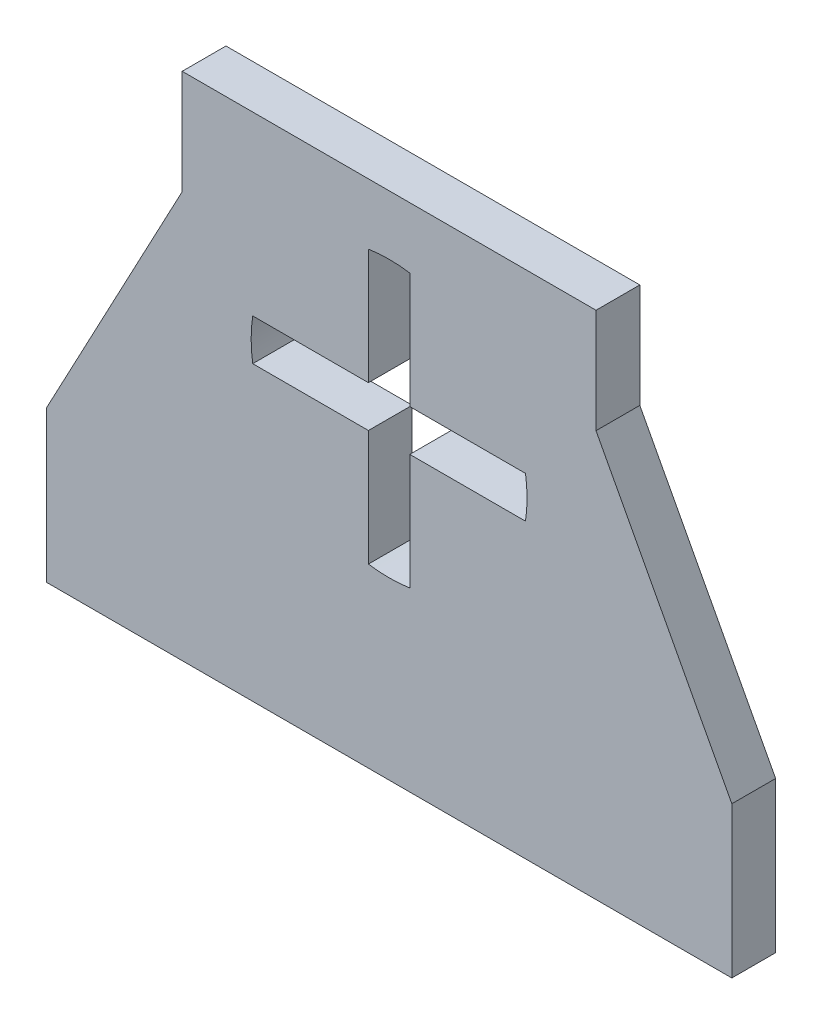
SolidWorks part; units mm, degrees
ref_plane "Front Plane" through (0, 0, 0) normal (0, 0, 1) x (1, 0, 0)
ref_plane "Top Plane" through (0, 0, 0) normal (0, 1, 0) x (1, 0, 0)
ref_plane "Right Plane" through (0, 0, 0) normal (1, 0, 0) x (0, 0, -1)
sketch "Sketch1" plane through (0, 0, 0) normal (0, 0, 1) x (1, 0, 0)
  line L1 (-24.845, 13.5) -> (24.845, 13.5)
  line L2 (-24.845, 13.5) -> (-24.845, -13.5)
  line L3 (-24.845, -13.5) -> (24.845, -13.5)
  line L4 (24.845, 13.5) -> (24.845, -13.5)
  line L5 (-24.845, 13.5) -> (24.845, -13.5) construction
  line L6 (-24.845, -13.5) -> (24.845, 13.5) construction
  point P0 (0, 0)
  dimension "D1" = 27
  dimension "D2" = 49.69
extrude "Boss-Extrude1" add sketch "Sketch1" along normal blind 3.175
sketch "Sketch2" plane through (0, 0, 0) normal (0, 0, 1) x (1, 0, 0)
  line L0 (24.845, -13.5) -> (-24.845, -13.5)
  line L1 (-24.845, -13.5) -> (-24.845, 13.5)
  line L2 (-24.845, 13.5) -> (24.845, 13.5)
  line L4 (24.845, 0) -> (24.845, 13.5)
  line L5 (24.845, 0) -> (24.845, -13.5)
  line L9 (0, 13.5) -> (10, 13.5)
  line L10 (0, 13.5) -> (-10, 13.5)
  line L11 (10, 13.5) -> (10, 6.75)
  line L12 (-10, 13.5) -> (-10, 6.75)
  line L13 (-10, 6.75) -> (-24.845, -6.75)
  line L14 (10, 6.75) -> (24.845, -6.75)
  dimension "D1" = 10
  dimension "D2" = 10
extrude "Cut-Extrude1" cut sketch "Sketch2" along normal blind 3.175 contours L11 L14 L5 L4 L2 | L13 L12 L2 L1
sketch "Sketch3" plane through (0, 0, 0) normal (0, 0, -1) x (-1, 0, 0)
  line L0 (-24.845, -13.5) -> (24.845, -13.5)
  line L1 (-10, 13.5) -> (-10, 23.5)
  line L2 (0, -0.8) -> (0, 9.2)
  line L3 (-24.845, -13.5) -> (-24.845, -6.75)
  line L4 (-24.845, -6.75) -> (-10, 6.75)
  line L5 (-10, 6.75) -> (-10, 13.5)
  line L6 (-10, 13.5) -> (10, 13.5)
  line L7 (10, 13.5) -> (10, 6.75)
  line L8 (10, 6.75) -> (24.845, -6.75)
  line L9 (24.845, -6.75) -> (24.845, -13.5)
  line L10 (10, 13.5) -> (10, 23.5)
  line L12 (10, 23.5) -> (-10, 23.5)
  line L13 (-10, 23.5) -> (-15, 23.5)
  line L14 (-15, 23.5) -> (-15, 15.9375)
  line L15 (15, 23.5) -> (15, 15.9375)
  line L16 (10, 23.5) -> (15, 23.5)
  line L20 (24.845, -2.5625) -> (24.845, -6.75)
  line L22 (-24.845, -2.5625) -> (-24.845, -13.5)
  line L23 (-24.845, -2.5625) -> (-15, 15.9375)
  line L24 (24.845, -2.5625) -> (15, 15.9375)
  circle A0 centre (0, 9.2) radius 10
  line M17 (-10, 13.5) -> (-10, 6.75)
  line M18 (-10, 6.75) -> (-24.845, -6.75)
  line M22 (24.845, -6.75) -> (10, 6.75)
  line M23 (10, 6.75) -> (10, 13.5)
  line M24 (10, 13.5) -> (-10, 13.5)
  dimension "D3" = 20
  dimension "D4" = 10
  dimension "D5" = 5
extrude "Boss-Extrude2" add sketch "Sketch3" against normal blind 3.175 contours L23 L22 L5 L1 L13 L14 M18 M17 | L20 L24 L15 L16 L10 L7 M23 M22 | A0 L10 L12 L1 M24
sketch "Sketch4" plane through (0, 0, 0) normal (0, 0, -1) x (-1, 0, 0)
  line L0 (-24.845, -13.5) -> (24.845, -13.5)
  line L1 (0, -13.5) -> (0, -3.8)
  line L2 (0, -3.8) -> (0, 9.2)
  circle A0 centre (0, 9.2) radius 10
  dimension "D3" = 20
  dimension "D1" = 9.7
  dimension "D2" = 13
extrude "Boss-Extrude3" add sketch "Sketch4" against normal blind 3.175
sketch "Sketch5" plane through (0, 0, 0) normal (0, 0, -1) x (-1, 0, 0)
  line L0 (0, -13.5) -> (0, -3.8)
  line L1 (24.845, -13.5) -> (-24.845, -13.5) construction
  line L2 (0, -3.8) -> (0, -0.8)
  line L5 (1, 10.2) -> (1, 19.1499)
  line L6 (1, 8.2) -> (1, -0.7499)
  line L7 (-1, 8.2) -> (-1, -0.7499)
  line L8 (-1, 10.2) -> (-1, 19.1499)
  line L11 (-9.9499, 8.2) -> (-1, 8.2)
  line L12 (-9.9499, 10.2) -> (-1, 10.2)
  line L14 (1, 8.2) -> (9.9499, 8.2)
  line L15 (1, 10.2) -> (9.9499, 10.2)
  circle A0 centre (0, 9.2) radius 10
  point P10 (0, 9.2)
  point P13 (0, 9.2)
  dimension "D3" = 20
  dimension "D1" = 9.7
  dimension "D2" = 13
extrude "Cut-Extrude2" cut sketch "Sketch5" against normal blind 3.175 contours L5 A0 L8 L12 L11 L7 L6 L14 L15
sketch "Sketch6" plane through (0, 0, 0) normal (0, 0, -1) x (-1, 0, 0)
  line L1 (10, 9.2) -> (8.2649, 9.2)
  line L2 (1.5, 19.0869) -> (1.5, 10.7)
  line L3 (1, -0.7499) -> (1, 8.2)
  line L5 (1.5, -0.6869) -> (1.5, 7.7)
  line L6 (1, 8.2) -> (9.9499, 8.2)
  line L7 (9.9499, 10.2) -> (1, 10.2)
  line L9 (-1.5, -0.6869) -> (-1.5, 7.7)
  line L10 (-1.5, 19.0869) -> (-1.5, 10.7)
  line L13 (9.8869, 7.7) -> (1.5, 7.7)
  line L14 (1, 10.2) -> (1, 19.1499)
  line L16 (-9.8869, 7.7) -> (-1.5, 7.7)
  line L18 (9.8869, 10.7) -> (1.5, 10.7)
  line L20 (-9.8869, 10.7) -> (-1.5, 10.7)
  line L21 (-1, 19.1499) -> (-1, 10.2)
  line L22 (-1, 10.2) -> (-9.9499, 10.2)
  line L23 (-9.9499, 8.2) -> (-1, 8.2)
  line L24 (-1, 8.2) -> (-1, -0.7499)
  line L25 (1, 8.2) -> (-1, 10.2)
  line L26 (-1, 8.2) -> (1, 10.2)
  circle A0 centre (0, 9.2) radius 10
  arc A1 (9.9499, 8.2) -> (9.9499, 10.2) centre (0, 9.2) ccw construction
extrude "Cut-Extrude3" cut sketch "Sketch6" against normal blind 3.175
